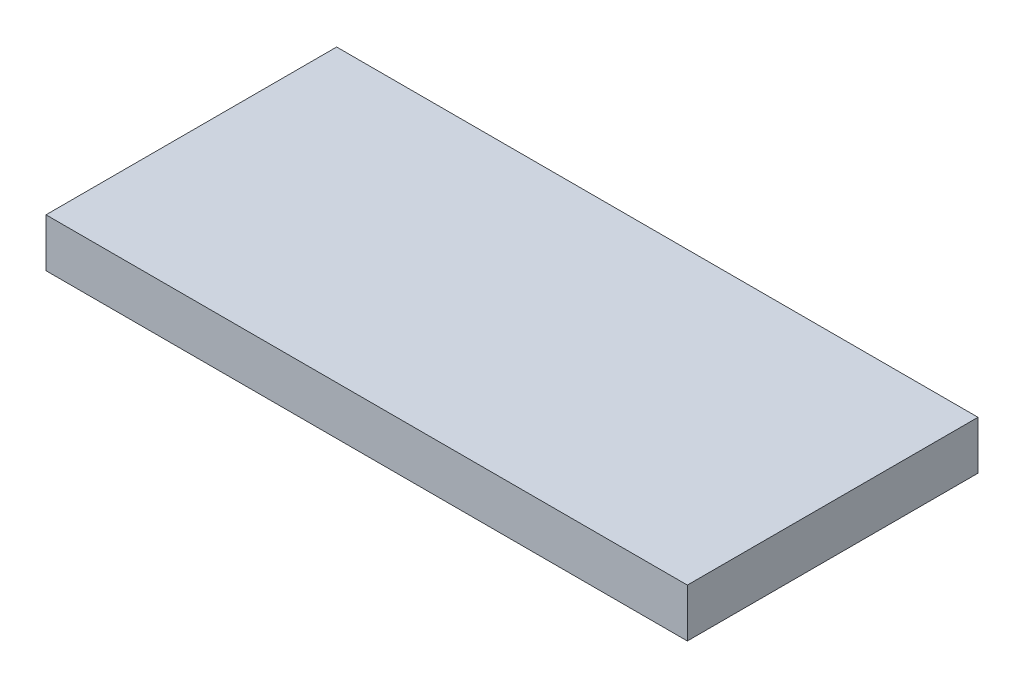
SolidWorks part; units mm, degrees
ref_plane "Front Plane" through (0, 0, 0) normal (0, 0, 1) x (1, 0, 0)
ref_plane "Top Plane" through (0, 0, 0) normal (0, 1, 0) x (1, 0, 0)
ref_plane "Right Plane" through (0, 0, 0) normal (1, 0, 0) x (0, 0, -1)
sketch "Sketch1" plane through (0, 0, 0) normal (0, 1, 0) x (1, 0, 0)
  line L1 (0, 0) -> (84.074, 0)
  line L2 (0, 0) -> (0, -38.1)
  line L3 (0, -38.1) -> (84.074, -38.1)
  line L4 (84.074, 0) -> (84.074, -38.1)
  dimension "D1" = 38.1
  dimension "D2" = 84.074
extrude "Boss-Extrude1" add sketch "Sketch1" along normal blind 6.35
